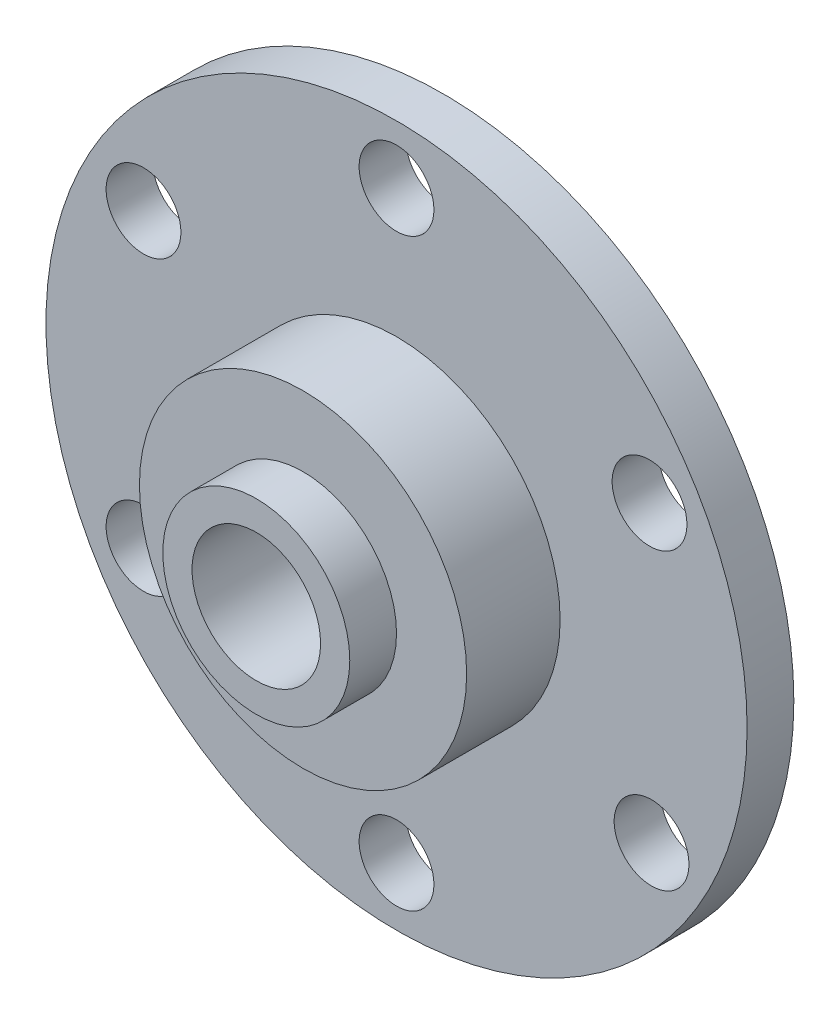
SolidWorks part; units mm, degrees
ref_plane "Plan de face" through (0, 0, 0) normal (0, 0, 1) x (1, 0, 0)
ref_plane "Plan de dessus" through (0, 0, 0) normal (0, 1, 0) x (1, 0, 0)
ref_plane "Plan de droite" through (0, 0, 0) normal (1, 0, 0) x (0, 0, -1)
sketch "Esquisse1" plane through (0, 0, 0) normal (0, 0, 1) x (1, 0, 0)
  line L0 (0, 0) -> (0, 12.5) construction
  line L1 (0, 12.5) -> (0, -12.5) construction
  line L2 (0, -12.5) -> (0, 0) construction
  line L3 (0, 0) -> (10.9119, -6.3) construction
  line L4 (10.9119, -6.3) -> (-10.8253, 6.25) construction
  line L5 (-10.8253, 6.25) -> (0, 0) construction
  line L6 (0, 0) -> (-10.8253, -6.25) construction
  line L7 (0, 0) -> (10.8253, 6.25) construction
  circle A0 centre (0, 0) radius 15
  circle A1 centre (0, 0) radius 12.5 construction
  circle A2 centre (0, 12.5) radius 1.6
  circle A3 centre (-10.8253, 6.25) radius 1.6
  circle A4 centre (-10.8253, -6.25) radius 1.6
  circle A5 centre (0, -12.5) radius 1.6
  circle A6 centre (10.9119, -6.3) radius 1.6
  circle A7 centre (10.8253, 6.25) radius 1.6
  circle A8 centre (0, 0) radius 2.75
  dimension "D1" = 60
  dimension "D3" = 3.2
  dimension "D5" = 5.5
  dimension "D7" = 30
  dimension "D2" = 60
  dimension "D4" = 12.5
  dimension "D6" = 60
extrude "Boss.-Extru.1" add sketch "Esquisse1" along normal blind 2 contours A0 A7 A6 A5 A4 A3 A2
sketch "Esquisse2" plane through (0, 0, 2) normal (0, 0, 1) x (1, 0, 0)
  circle A0 centre (0, 0) radius 2.75
  circle A1 centre (0, 0) radius 7
extrude "Boss.-Extru.2" add sketch "Esquisse2" along normal blind 4
sketch "Esquisse3" plane through (0, 0, 6) normal (0, 0, 1) x (1, 0, 0)
  circle A0 centre (0, 0) radius 2.75
  circle A1 centre (0, 0) radius 4
extrude "Boss.-Extru.3" add sketch "Esquisse3" along normal blind 2
